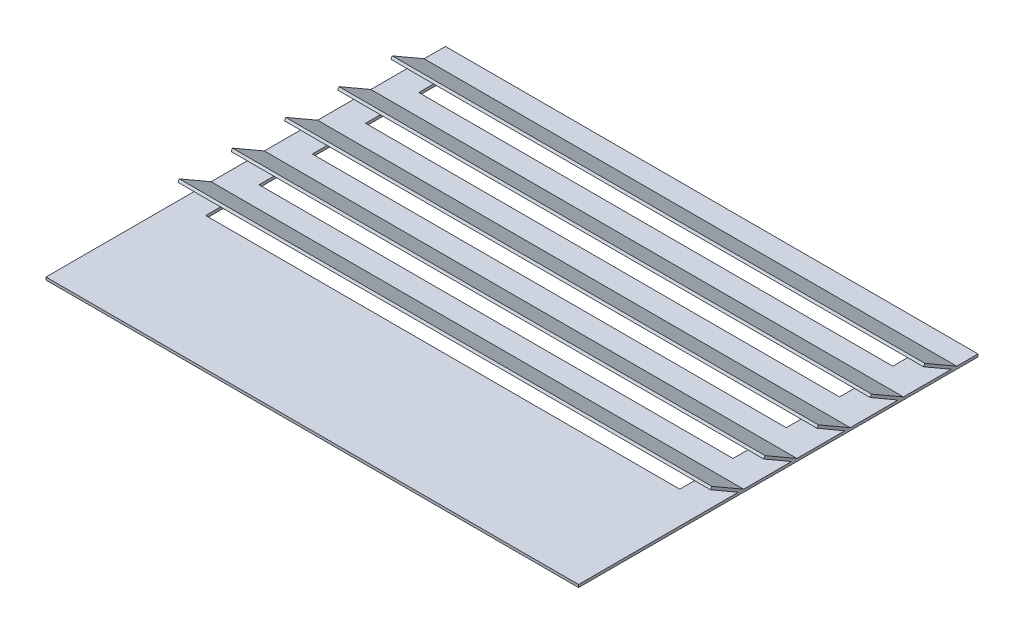
SolidWorks part; units mm, degrees
ref_plane "前视基准面" through (0, 0, 0) normal (0, 0, 1) x (1, 0, 0)
ref_plane "上视基准面" through (0, 0, 0) normal (0, 1, 0) x (1, 0, 0)
ref_plane "右视基准面" through (0, 0, 0) normal (1, 0, 0) x (0, 0, -1)
sketch "草图1" plane through (0, 0, 0) normal (0, 1, 0) x (1, 0, 0)
  line L1 (0, 0) -> (200, 0)
  line L2 (0, 0) -> (0, -150)
  line L3 (0, -150) -> (200, -150)
  line L4 (200, 0) -> (200, -150)
  dimension "D1" = 200
  dimension "D2" = 150
extrude "凸台-拉伸1" add sketch "草图1" along normal blind 1
sketch "草图3" plane through (0, 0, 0) normal (1, 0, 0) x (0, 0, -1)
  line L0 (-10, 1) -> (-20.4673, 7.0433)
  line L1 (-20.4673, 7.0433) -> (-19.9673, 7.9093)
  line L2 (-19.9673, 7.9093) -> (-8, 1)
  line L3 (-8, 1) -> (-10, 1)
  line B0 (-150, 1) -> (0, 1)
  line B1 (-150, -199) -> (0, -199)
  line B2 (-150, -199) -> (-150, 1)
  line B3 (0, -199) -> (0, 1)
  line B4 (-150, -197) -> (-2, -197) construction
  line B5 (-2, -197) -> (-2, -1) construction
  line B6 (-150, -1) -> (-2, -1) construction
  line B7 (-90, 1) -> (-90, -1) construction
  line B8 (-70, 1) -> (-70, -1) construction
  line B9 (-90, -197) -> (-90, -199) construction
  line B10 (-70, -197) -> (-70, -199) construction
  line B11 (-10, -197) -> (-10, -199) construction
  line B12 (-30, 1) -> (-30, -1) construction
  line B13 (-50, 1) -> (-50, -1) construction
  line B14 (-10, 1) -> (-10, -1) construction
  line B15 (-50, -197) -> (-50, -199) construction
  line B16 (-30, -197) -> (-30, -199) construction
  line B17 (-80, -197) -> (-80, -199) construction
  line B18 (-20, -197) -> (-20, -199) construction
  line B19 (-20, 1) -> (-20, -1) construction
  line B20 (-80, 1) -> (-80, -1) construction
  line B21 (-40, 1) -> (-40, -1) construction
  line B22 (-100, 1) -> (-100, -1) construction
  line B23 (-40, -197) -> (-40, -199) construction
  line B24 (-60, 1) -> (-60, -1) construction
  line B25 (-100, -197) -> (-100, -199) construction
  line B26 (-60, -197) -> (-60, -199) construction
  line B27 (0, -12.25) -> (-2, -12.25) construction
  line B28 (-2, -15.75) -> (0, -15.75) construction
  line B29 (0, -182.25) -> (-2, -182.25) construction
  line B30 (-2, -185.75) -> (0, -185.75) construction
  line B31 (0, -3.614) -> (-2, -3.614) construction
  line B32 (-2, -7.114) -> (0, -7.114) construction
  line B33 (0, -190.886) -> (-2, -190.886) construction
  line B34 (-2, -194.386) -> (0, -194.386) construction
  dimension "D1" = 30
  dimension "D2" = 1
sketch_block_instance "box-1"
sketch_block "块1"
sketch "草图4" plane through (0, 0, 0) normal (-1, 0, 0) x (0, 0, 1)
  line L17 (8, 1) -> (10, 1)
  line L18 (20.4673, 7.0433) -> (19.9673, 7.9093)
  line L19 (19.9673, 7.9093) -> (8, 1)
  line L20 (10, 1) -> (20.4673, 7.0433)
  line L21 (8, 1) -> (10, 1)
  line L22 (20.4673, 7.0433) -> (19.9673, 7.9093)
  line L23 (19.9673, 7.9093) -> (8, 1)
  line L24 (10, 1) -> (20.4673, 7.0433)
  dimension "D1" = 0
extrude "凸台-拉伸2" add sketch "草图4" against normal blind 200
pattern_linear "阵列(线性)1" count 5 spacing 20 along (0, 0, 1) of "凸台-拉伸2"
sketch "草图5" plane through (0, 1, 0) normal (0, 1, 0) x (1, 0, 0)
  line L0 (200, 0) -> (0, 0) construction
  line L1 (10, -10) -> (188, -10)
  line L2 (10, -10) -> (10, -20)
  line L3 (10, -20) -> (188, -20)
  line L4 (188, -10) -> (188, -20)
  line L5 (0, -19.9673) -> (0, -8) construction
  line L6 (200, -19.9673) -> (200, -8) construction
  dimension "D1" = 10
  dimension "D2" = 10
  dimension "D3" = 12
  dimension "D4" = 10
extrude "切除-拉伸1" cut sketch "草图5" against normal blind 1
pattern_linear "阵列(线性)2" count 5 spacing 20 along (0, 0, 1) of "切除-拉伸1"
